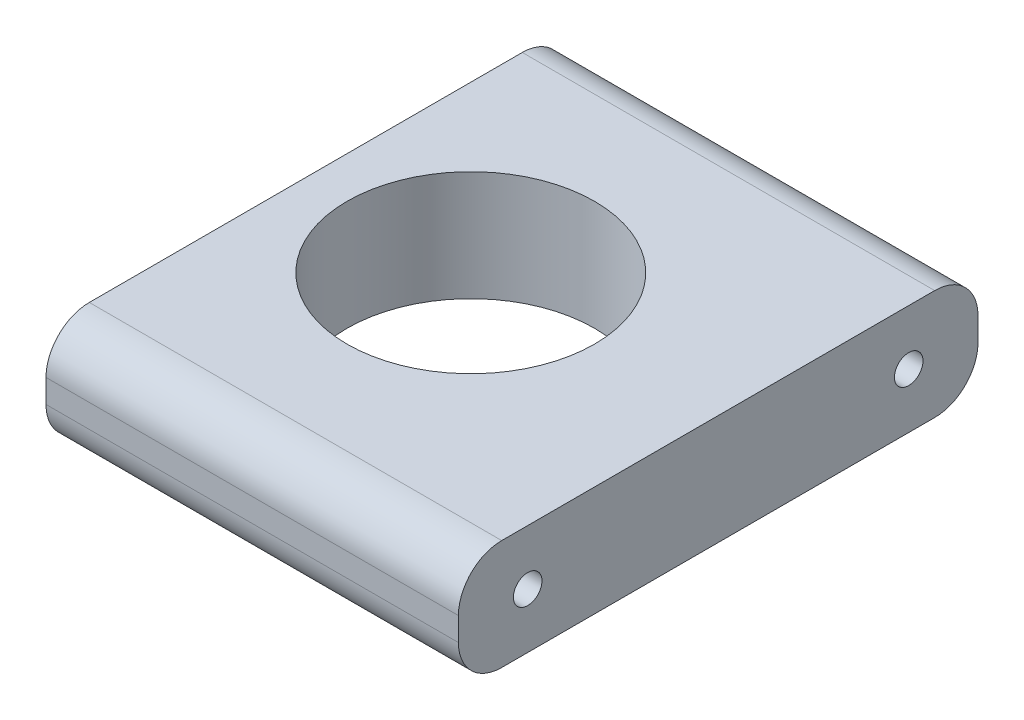
SolidWorks part; units mm, degrees
material "6061 Alloy"
ref_plane "Front Plane" through (0, 0, 0) normal (0, 0, 1) x (1, 0, 0)
ref_plane "Top Plane" through (0, 0, 0) normal (0, 1, 0) x (1, 0, 0)
ref_plane "Right Plane" through (0, 0, 0) normal (1, 0, 0) x (0, 0, -1)
sketch "Sketch2" plane through (0, 0, 0) normal (0, 1, 0) x (1, 0, 0)
  line L0 (0, 0) -> (23.81, 0)
  line L1 (23.81, 0) -> (23.81, 22.6)
  line L2 (23.81, 22.6) -> (36.51, 22.6)
  line L3 (36.51, 22.6) -> (36.51, 61.175)
  line L4 (36.51, 61.175) -> (-11.11, 61.175)
  line L5 (-11.11, 61.175) -> (-11.11, 22.6)
  line L6 (-11.11, 22.6) -> (0, 22.6)
  line L7 (0, 22.6) -> (0, 0)
  line L8 (12.7, 61.175) -> (12.7, 41.8875)
  line L9 (23.81, 0) -> (3.31, 0)
  line L10 (3.31, 0) -> (3.31, 22.6)
  line L11 (3.31, 22.6) -> (23.81, 22.6)
  line L12 (3.31, 22.6) -> (0, 22.6)
  line L13 (0, 0) -> (-23.373, 0)
  line L14 (-23.373, 0) -> (-23.373, 5.1324)
  line L15 (-23.373, 5.1324) -> (0, 5.1324)
  line L16 (1.585, 0) -> (1.585, 22.6)
  line L17 (23.81, 0) -> (30.16, 0)
  line L18 (30.16, 0) -> (30.16, 22.6)
  line L19 (30.16, 0) -> (23.81, 0)
  line L20 (0, 0) -> (-6.3525, 0)
  line L21 (-6.3525, 0) -> (-6.3525, 22.6)
  line L22 (-6.3525, 22.6) -> (-6.3525, 61.175)
  line L23 (36.51, 22.6) -> (36.51, 11.3)
  line L24 (12.7, 11.8875) -> (36.51, 11.8875)
  line L25 (12.7, 11.8875) -> (-6.3525, 11.8875)
  line L26 (36.51, 61.175) -> (36.51, 72.475)
  line L27 (12.7, 71.8875) -> (36.51, 71.8875)
  line L28 (-6.3525, 72.475) -> (-6.3525, 61.175)
  line L29 (12.7, 41.8875) -> (12.7, 11.8875)
  line L30 (12.7, 41.8875) -> (12.7, 71.8875)
  line L31 (12.7, 71.8875) -> (-6.3525, 71.8875)
  line L32 (36.51, 71.8875) -> (41.2725, 71.8875)
  line L33 (41.2725, 71.8875) -> (41.2725, 11.8875)
  line L34 (41.2725, 11.8875) -> (36.51, 11.8875)
  circle A0 centre (12.7, 41.8875) radius 14.2875
  dimension "D7" = 28.575
  dimension "D1" = 22.6
  dimension "D2" = 38.575
  dimension "D3" = 12.7
  dimension "D4" = 11.11
  dimension "D5" = 23.81
  dimension "D6" = 19.2875
  dimension "D8" = 20.5
  dimension "D9" = 1.585
  dimension "D10" = 28.575
  dimension "D11" = 7.9375
  dimension "D12" = 11.3
  dimension "D13" = 30
  dimension "D14" = 30
  dimension "D15" = 47.625
extrude "Boss-Extrude1" add sketch "Sketch2" along normal blind 12.7 contours L30 L4 L26 L27 | L30 L31 L28 L4 | A0 L8 L4 L22 L6 L12 L11 L29 | A0 L29 L11 L2 L3 L4 L8 | L11 L29 L24 L1 | L29 L11 L10 L25 | L1 L24 L18 L2 | L18 L24 L23 L2 | L25 L10 L12 L16 | L25 L16 L12 L7 | L25 L7 L6 L21 | L34 L33 L32 L26 L3 L23
sketch "Sketch4" plane through (41.2725, 0, 0) normal (1, 0, 0) x (0, 0, -1)
  line L0 (11.8875, 6.35) -> (19.8875, 6.35)
  line L2 (71.8875, 6.35) -> (63.8875, 6.35)
  line L4 (71.8875, 12.7) -> (71.8875, 0) construction
  line L5 (11.8875, 12.7) -> (11.8875, 0) construction
  point P1 (19.8875, 6.35)
  point P5 (63.8875, 6.35)
  dimension "D1" = 8
hole_wizard "M4x0.7 Tapped Hole1" positions "Sketch4" profile "Sketch6" tap size "M4x0.7" standard "ANSI Metric" end condition through all
sketch "Sketch6" plane through (41.2725, 6.35, -63.8875) normal (0, 1, 0) x (0, 0, -1)
  line L0 (0, 0) -> (0, 47.625)
  line L1 (0, 47.625) -> (1.65, 47.625)
  line L2 (1.65, 47.625) -> (1.65, 0)
  line L5 (1.65, 0) -> (0, 0)
  line L11 (0, -6.35) -> (0, 107.95) construction
  dimension "Thru Tap Drill Dia." = 3.3
  dimension "Thru Tap Drill Depth" = 47.625
cosmetic thread "Hole Thread3" parameters "D2"=4
cosmetic thread "Hole Thread4" parameters "D2"=4
fillet "Fillet1" radius 5 4 edges at (17.46, 0, -11.8875) (17.46, 12.7, -11.8875) (17.46, 0, -71.8875) (17.46, 12.7, -71.8875)
